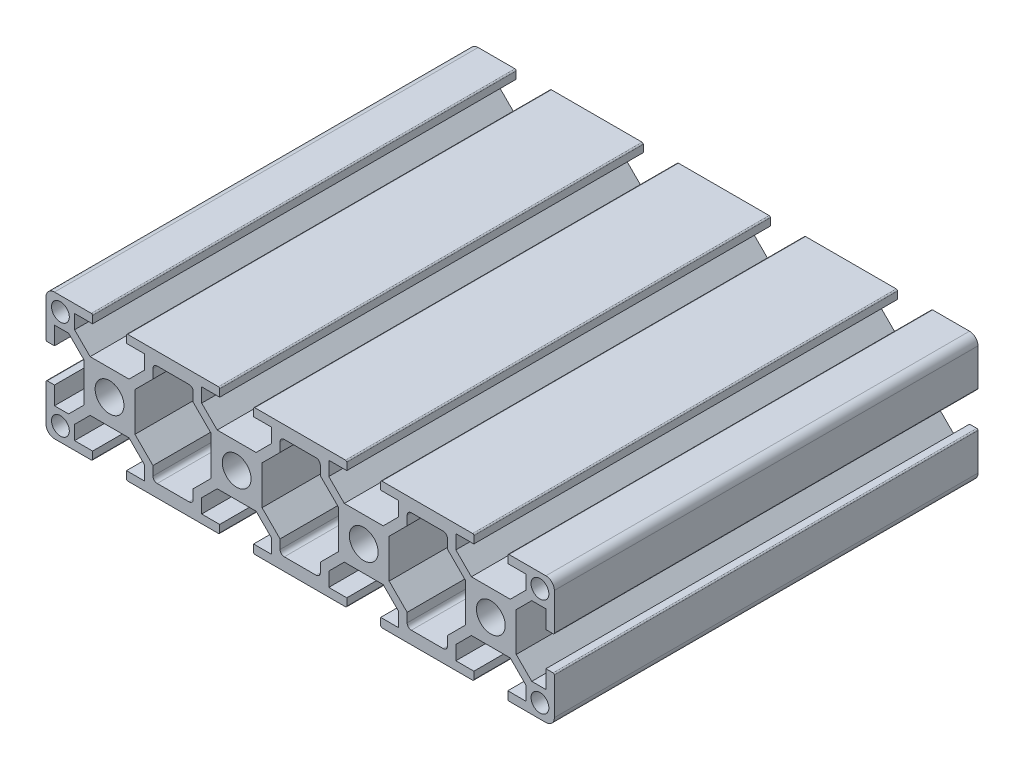
SolidWorks part; units mm, degrees
ref_plane "前视基准面" through (0, 0, 0) normal (0, 0, 1) x (1, 0, 0)
ref_plane "上视基准面" through (0, 0, 0) normal (0, 1, 0) x (1, 0, 0)
ref_plane "右视基准面" through (0, 0, 0) normal (1, 0, 0) x (0, 0, -1)
sketch "草图1" plane through (0, 0, 0) normal (0, 0, 1) x (1, 0, 0)
  line B0 (55.4142, 6) -> (51.75, 9.6642) construction
  line B1 (54, 4.5858) -> (49.75, 8.8358) construction
  line B2 (24, -4.5858) -> (24, 4.5858) construction
  line B3 (36, 4.5858) -> (36, -4.5858) construction
  line B4 (69.6642, 8.25) -> (66, 4.5858) construction
  line B5 (66, -4.5858) -> (66, 4.5858) construction
  line B6 (55.4142, 6) -> (51.75, 9.6642) construction
  line B7 (68.25, 9.6642) -> (64.5858, 6) construction
  line B8 (66, 4.5858) -> (70.25, 8.8358) construction
  line B9 (60, 6) -> (64.5858, 6) construction
  line B10 (64.5858, 6) -> (68.25, 9.6642) construction
  line B11 (24, -4.5858) -> (24, 4.5858) construction
  line B12 (70.25, 11) -> (70.25, 10)
  line B13 (70.25, 10) -> (70.25, 8.8358)
  line B14 (70.25, 8.8358) -> (66, 4.5858)
  line B15 (66, 4.5858) -> (66, -4.5858)
  line B16 (66, -4.5858) -> (70.25, -8.8358)
  line B17 (70.25, -8.8358) -> (70.25, -10)
  line B18 (70.25, -10) -> (70.25, -11)
  line B19 (71.25, -12) -> (78.75, -12)
  line B20 (79.75, -11) -> (79.75, -10)
  line B21 (79.75, -10) -> (79.75, -8.8358)
  line B22 (79.75, -8.8358) -> (84, -4.5858)
  line B23 (84, -4.5858) -> (84, 4.5858)
  line B24 (84, 4.5858) -> (79.75, 8.8358)
  line B25 (79.75, 8.8358) -> (79.75, 10)
  line B26 (79.75, 10) -> (79.75, 11)
  line B27 (78.75, 12) -> (71.25, 12)
  line B28 (-15, 13) -> (-15, 4.3)
  line B29 (-14.7, 4) -> (-13, 4)
  line B30 (-13, 4) -> (-13, 8.25)
  line B31 (-13, 8.25) -> (-9.6642, 8.25)
  line B32 (-9.6642, 8.25) -> (-6, 4.5858)
  line B33 (-6, 4.5858) -> (-6, -4.5858)
  line B34 (-6, -4.5858) -> (-9.6642, -8.25)
  line B35 (-9.6642, -8.25) -> (-13, -8.25)
  line B36 (-13, -8.25) -> (-13, -4)
  line B37 (-13, -4) -> (-14.7, -4)
  line B38 (-15, -4.3) -> (-15, -13)
  line B39 (-13, -15) -> (-4.3, -15)
  line B40 (-4, -14.7) -> (-4, -13)
  line B41 (-4, -13) -> (-8.25, -13)
  line B42 (-8.25, -13) -> (-8.25, -9.6642)
  line B43 (-8.25, -9.6642) -> (-4.5858, -6)
  line B44 (-4.5858, -6) -> (4.5858, -6)
  line B45 (4.5858, -6) -> (8.25, -9.6642)
  line B46 (8.25, -9.6642) -> (8.25, -13)
  line B47 (8.25, -13) -> (4, -13)
  line B48 (4, -13) -> (4, -14.7)
  line B49 (4.3, -15) -> (25.7, -15)
  line B50 (26, -14.7) -> (26, -13)
  line B51 (26, -13) -> (21.75, -13)
  line B52 (21.75, -13) -> (21.75, -9.6642)
  line B53 (21.75, -9.6642) -> (25.4142, -6)
  line B54 (25.4142, -6) -> (34.5858, -6)
  line B55 (34.5858, -6) -> (38.25, -9.6642)
  line B56 (38.25, -9.6642) -> (38.25, -13)
  line B57 (38.25, -13) -> (34, -13)
  line B58 (34, -13) -> (34, -14.7)
  line B59 (34.3, -15) -> (55.7, -15)
  line B60 (56, -14.7) -> (56, -13)
  line B61 (56, -13) -> (51.75, -13)
  line B62 (51.75, -13) -> (51.75, -9.6642)
  line B63 (51.75, -9.6642) -> (55.4142, -6)
  line B64 (55.4142, -6) -> (64.5858, -6)
  line B65 (64.5858, -6) -> (68.25, -9.6642)
  line B66 (68.25, -9.6642) -> (68.25, -13)
  line B67 (68.25, -13) -> (64, -13)
  line B68 (64, -13) -> (64, -14.7)
  line B69 (64.3, -15) -> (85.7, -15)
  line B70 (86, -14.7) -> (86, -13)
  line B71 (86, -13) -> (81.75, -13)
  line B72 (81.75, -13) -> (81.75, -9.6642)
  line B73 (81.75, -9.6642) -> (85.4142, -6)
  line B74 (85.4142, -6) -> (94.5858, -6)
  line B75 (94.5858, -6) -> (98.25, -9.6642)
  line B76 (98.25, -9.6642) -> (98.25, -13)
  line B77 (98.25, -13) -> (94, -13)
  line B78 (94, -13) -> (94, -14.7)
  line B79 (94.3, -15) -> (103, -15)
  line B80 (105, -13) -> (105, -4.3)
  line B81 (104.7, -4) -> (103, -4)
  line B82 (103, -4) -> (103, -8.25)
  line B83 (103, -8.25) -> (99.6642, -8.25)
  line B84 (99.6642, -8.25) -> (96, -4.5858)
  line B85 (96, -4.5858) -> (96, 4.5858)
  line B86 (96, 4.5858) -> (99.6642, 8.25)
  line B87 (99.6642, 8.25) -> (103, 8.25)
  line B88 (103, 8.25) -> (103, 4)
  line B89 (103, 4) -> (104.7, 4)
  line B90 (105, 4.3) -> (105, 13)
  line B91 (103, 15) -> (94.3, 15)
  line B92 (94, 14.7) -> (94, 13)
  line B93 (94, 13) -> (98.25, 13)
  line B94 (98.25, 13) -> (98.25, 9.6642)
  line B95 (98.25, 9.6642) -> (94.5858, 6)
  line B96 (94.5858, 6) -> (85.4142, 6)
  line B97 (85.4142, 6) -> (81.75, 9.6642)
  line B98 (81.75, 9.6642) -> (81.75, 13)
  line B99 (81.75, 13) -> (86, 13)
  line B100 (86, 13) -> (86, 14.7)
  line B101 (85.7, 15) -> (64.3, 15)
  line B102 (64, 14.7) -> (64, 13)
  line B103 (64, 13) -> (68.25, 13)
  line B104 (68.25, 13) -> (68.25, 9.6642)
  line B105 (68.25, 9.6642) -> (64.5858, 6)
  line B106 (64.5858, 6) -> (55.4142, 6)
  line B107 (55.4142, 6) -> (51.75, 9.6642)
  line B108 (51.75, 9.6642) -> (51.75, 13)
  line B109 (51.75, 13) -> (56, 13)
  line B110 (56, 13) -> (56, 14.7)
  line B111 (55.7, 15) -> (34.3, 15)
  line B112 (34, 14.7) -> (34, 13)
  line B113 (34, 13) -> (38.25, 13)
  line B114 (38.25, 13) -> (38.25, 9.6642)
  line B115 (38.25, 9.6642) -> (34.5858, 6)
  line B116 (34.5858, 6) -> (25.4142, 6)
  line B117 (25.4142, 6) -> (21.75, 9.6642)
  line B118 (21.75, 9.6642) -> (21.75, 13)
  line B119 (21.75, 13) -> (26, 13)
  line B120 (26, 13) -> (26, 14.7)
  line B121 (25.7, 15) -> (4.3, 15)
  line B122 (4, 14.7) -> (4, 13)
  line B123 (4, 13) -> (8.25, 13)
  line B124 (8.25, 13) -> (8.25, 9.6642)
  line B125 (8.25, 9.6642) -> (4.5858, 6)
  line B126 (4.5858, 6) -> (-4.5858, 6)
  line B127 (-4.5858, 6) -> (-8.25, 9.6642)
  line B128 (-8.25, 9.6642) -> (-8.25, 13)
  line B129 (-8.25, 13) -> (-4, 13)
  line B130 (-4, 13) -> (-4, 14.7)
  line B131 (-4.3, 15) -> (-13, 15)
  line B132 (11.25, -12) -> (18.75, -12)
  line B133 (19.75, -11) -> (19.75, -10)
  line B134 (19.75, -10) -> (19.75, -8.8358)
  line B135 (19.75, -8.8358) -> (24, -4.5858)
  line B136 (24, -4.5858) -> (24, 4.5858)
  line B137 (24, 4.5858) -> (19.75, 8.8358)
  line B138 (19.75, 8.8358) -> (19.75, 10)
  line B139 (19.75, 10) -> (19.75, 11)
  line B140 (18.75, 12) -> (11.25, 12)
  line B141 (10.25, 11) -> (10.25, 10)
  line B142 (10.25, 10) -> (10.25, 8.8358)
  line B143 (10.25, 8.8358) -> (6, 4.5858)
  line B144 (6, 4.5858) -> (6, -4.5858)
  line B145 (6, -4.5858) -> (10.25, -8.8358)
  line B146 (10.25, -8.8358) -> (10.25, -10)
  line B147 (10.25, -10) -> (10.25, -11)
  line B148 (41.25, -12) -> (48.75, -12)
  line B149 (49.75, -11) -> (49.75, -10)
  line B150 (49.75, -10) -> (49.75, -8.8358)
  line B151 (49.75, -8.8358) -> (54, -4.5858)
  line B152 (54, -4.5858) -> (54, 4.5858)
  line B153 (54, 4.5858) -> (49.75, 8.8358)
  line B154 (49.75, 8.8358) -> (49.75, 10)
  line B155 (49.75, 10) -> (49.75, 11)
  line B156 (48.75, 12) -> (41.25, 12)
  line B157 (40.25, 11) -> (40.25, 10)
  line B158 (40.25, 10) -> (40.25, 8.8358)
  line B159 (40.25, 8.8358) -> (36, 4.5858)
  line B160 (36, 4.5858) -> (36, -4.5858)
  line B161 (36, -4.5858) -> (40.25, -8.8358)
  line B162 (40.25, -8.8358) -> (40.25, -10)
  line B163 (40.25, -10) -> (40.25, -11)
  arc B164 (71.25, 12) -> (70.25, 11) centre (71.25, 11) ccw
  arc B165 (70.25, -11) -> (71.25, -12) centre (71.25, -11) ccw
  arc B166 (78.75, -12) -> (79.75, -11) centre (78.75, -11) ccw
  arc B167 (79.75, 11) -> (78.75, 12) centre (78.75, 11) ccw
  arc B168 (-13, 15) -> (-15, 13) centre (-13, 13) ccw
  arc B169 (-15, 4.3) -> (-14.7, 4) centre (-14.7, 4.3) ccw
  arc B170 (-14.7, -4) -> (-15, -4.3) centre (-14.7, -4.3) ccw
  arc B171 (-15, -13) -> (-13, -15) centre (-13, -13) ccw
  arc B172 (-4.3, -15) -> (-4, -14.7) centre (-4.3, -14.7) ccw
  arc B173 (4, -14.7) -> (4.3, -15) centre (4.3, -14.7) ccw
  arc B174 (25.7, -15) -> (26, -14.7) centre (25.7, -14.7) ccw
  arc B175 (34, -14.7) -> (34.3, -15) centre (34.3, -14.7) ccw
  arc B176 (55.7, -15) -> (56, -14.7) centre (55.7, -14.7) ccw
  arc B177 (64, -14.7) -> (64.3, -15) centre (64.3, -14.7) ccw
  arc B178 (85.7, -15) -> (86, -14.7) centre (85.7, -14.7) ccw
  arc B179 (94, -14.7) -> (94.3, -15) centre (94.3, -14.7) ccw
  arc B180 (103, -15) -> (105, -13) centre (103, -13) ccw
  arc B181 (105, -4.3) -> (104.7, -4) centre (104.7, -4.3) ccw
  arc B182 (104.7, 4) -> (105, 4.3) centre (104.7, 4.3) ccw
  arc B183 (105, 13) -> (103, 15) centre (103, 13) ccw
  arc B184 (94.3, 15) -> (94, 14.7) centre (94.3, 14.7) ccw
  arc B185 (86, 14.7) -> (85.7, 15) centre (85.7, 14.7) ccw
  arc B186 (64.3, 15) -> (64, 14.7) centre (64.3, 14.7) ccw
  arc B187 (56, 14.7) -> (55.7, 15) centre (55.7, 14.7) ccw
  arc B188 (34.3, 15) -> (34, 14.7) centre (34.3, 14.7) ccw
  arc B189 (26, 14.7) -> (25.7, 15) centre (25.7, 14.7) ccw
  arc B190 (4.3, 15) -> (4, 14.7) centre (4.3, 14.7) ccw
  arc B191 (-4, 14.7) -> (-4.3, 15) centre (-4.3, 14.7) ccw
  arc B192 (10.25, -11) -> (11.25, -12) centre (11.25, -11) ccw
  arc B193 (18.75, -12) -> (19.75, -11) centre (18.75, -11) ccw
  arc B194 (19.75, 11) -> (18.75, 12) centre (18.75, 11) ccw
  arc B195 (11.25, 12) -> (10.25, 11) centre (11.25, 11) ccw
  arc B196 (40.25, -11) -> (41.25, -12) centre (41.25, -11) ccw
  arc B197 (48.75, -12) -> (49.75, -11) centre (48.75, -11) ccw
  arc B198 (49.75, 11) -> (48.75, 12) centre (48.75, 11) ccw
  arc B199 (41.25, 12) -> (40.25, 11) centre (41.25, 11) ccw
  circle B200 centre (60, 0) radius 3.4
  circle B201 centre (90, 0) radius 3.4
  circle B202 centre (30, 0) radius 3.4
  circle B203 centre (0, 0) radius 3.4
  circle B204 centre (30, 0) radius 3.4
  circle B205 centre (101.6, 11.65) radius 2.1
  circle B206 centre (101.6, -11.65) radius 2.1
  circle B207 centre (-11.6, -11.65) radius 2.1
  circle B208 centre (-11.6, 11.65) radius 2.1
  circle B209 centre (30, 0) radius 3.4
sketch_block_instance "A$C02F85F8F-1"
sketch_block "A$C02F85F8F"
extrude "凸台-拉伸1" add sketch "草图1" along normal blind 100 contours B130 B191 B131 B168 B28 B169 B29 B30 B31 B32 B33 B34 B35 B36 B37 B170 B38 B171 B39 B172 B40 B41 B42 B43 B44 B45 B46 B47 B48 B173 B49 B174 B50 B51 B52 B53 B54 B55 B56 B57 B58 B175 B59 B176 B60 B61 B62 B63 B64 B65 B66
